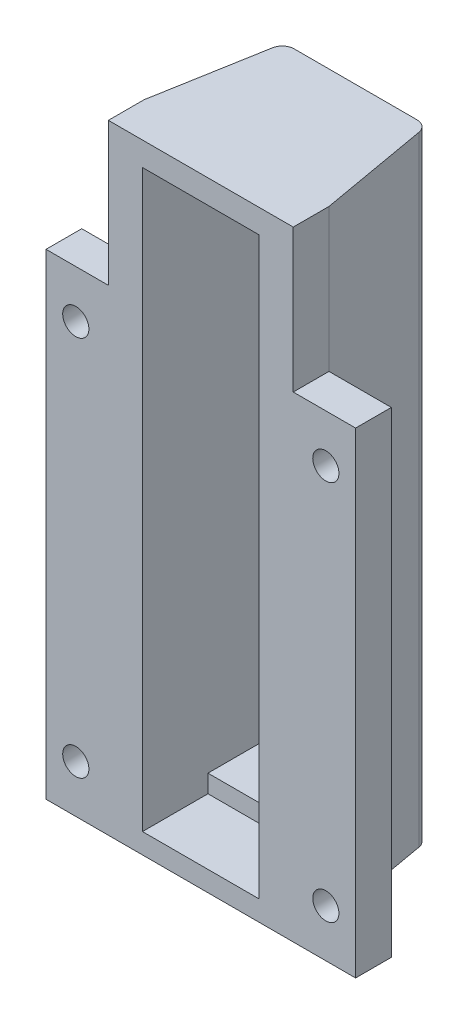
SolidWorks part; units mm, degrees
ref_plane "前视基准面" through (0, 0, 0) normal (0, 0, 1) x (1, 0, 0)
ref_plane "上视基准面" through (0, 0, 0) normal (0, 1, 0) x (1, 0, 0)
ref_plane "右视基准面" through (0, 0, 0) normal (1, 0, 0) x (0, 0, -1)
sketch "草图1" plane through (0, 0, 0) normal (0, 1, 0) x (1, 0, 0)
  line L0 (0, 0) -> (0, 11.5) construction
  line L1 (-13, -1.5) -> (13, -1.5)
  line L2 (-13, -1.5) -> (-13, 1.5)
  line L3 (-13, 1.5) -> (13, 1.5)
  line L4 (13, -1.5) -> (13, 1.5)
  line L5 (-13, -1.5) -> (13, 1.5) construction
  line L6 (-13, 1.5) -> (13, -1.5) construction
  line L7 (-6, 11.5) -> (6, 11.5)
  line L8 (6, 11.5) -> (8.2923, -1.5)
  line L9 (-6, 11.5) -> (-8.2923, -1.5)
  point P0 (0, 0)
  dimension "D1" = 26
  dimension "D2" = 3
  dimension "D3" = 80
  dimension "D4" = 12
  dimension "D5" = 13
extrude "凸台-拉伸1" add sketch "草图1" along normal blind 40 contours L7 L9 L3 L8 | L3 L9 L1 L8 | L9 L3 L2 L1 | L3 L8 L1 L4
sketch "草图2" plane through (0, 40, 0) normal (0, 1, 0) x (1, 0, 0)
  line L0 (6, 11.5) -> (7.7633, 1.5) construction
  line L1 (-6, 11.5) -> (6, 11.5) construction
  line L2 (-6, 11.5) -> (-7.7633, 1.5) construction
  line L3 (6, 11.5) -> (7.7633, 1.5)
  line L4 (-6, 11.5) -> (6, 11.5)
  line L5 (-6, 11.5) -> (-7.7633, 1.5)
  line L6 (-7.7633, 1.5) -> (-7.7633, -1.5)
  line L7 (-13, -1.5) -> (13, -1.5) construction
  line L8 (-7.7633, -1.5) -> (7.7633, -1.5)
  line L9 (7.7633, -1.5) -> (7.7633, 1.5)
extrude "凸台-拉伸2" add sketch "草图2" along normal blind 12
sketch "草图3" plane through (0, 0, 1.5) normal (0, 0, 1) x (1, 0, 0)
  line L0 (0, 0) -> (0, 25.85) construction
  line L1 (-7.7633, 52) -> (7.7633, 52) construction
  line L2 (-4.9, 3.2) -> (4.9, 3.2)
  line L3 (-4.9, 3.2) -> (-4.9, 48.5)
  line L4 (-4.9, 48.5) -> (4.9, 48.5)
  line L5 (4.9, 3.2) -> (4.9, 48.5)
  line L6 (-4.9, 3.2) -> (4.9, 48.5) construction
  line L7 (-4.9, 48.5) -> (4.9, 3.2) construction
  dimension "D1" = 9.8
  dimension "D2" = 45.3
  dimension "D3" = 3.5
extrude "切除-拉伸1" cut sketch "草图3" against normal offset from surface (10 mm away) 3 up to face at (0, 26, -11.5)
sketch "草图4" plane through (0, 0, 1.5) normal (0, 0, 1) x (1, 0, 0)
  line L0 (0, 48.5) -> (0, 3.2) construction
  line L2 (-4.9, 1.7) -> (4.9, 1.7)
  line L3 (-4.9, 1.7) -> (-4.9, 50)
  line L4 (4.9, 3.2) -> (4.9, 48.5)
  line L5 (4.9, 48.5) -> (-4.9, 48.5)
  line L6 (-4.9, 48.5) -> (-4.9, 3.2)
  line L7 (-4.9, 3.2) -> (4.9, 3.2)
  line L8 (4.9, 3.2) -> (4.9, 48.5) construction
  line L9 (4.9, 48.5) -> (-4.9, 48.5) construction
  line L10 (-4.9, 48.5) -> (-4.9, 3.2) construction
  line L11 (-4.9, 3.2) -> (4.9, 3.2) construction
  line L12 (-4.9, 50) -> (4.9, 50)
  line L13 (4.9, 1.7) -> (4.9, 50)
  line L14 (-4.9, 1.7) -> (4.9, 50) construction
  line L15 (-4.9, 50) -> (4.9, 1.7) construction
  point P6 (0, 25.85)
  point P11 (6.2017, 50)
  dimension "D2" = 1.5
  dimension "D1" = 0
extrude "切除-拉伸2" cut sketch "草图4" against normal offset from surface (5.5 mm away) 4.5 up to face at (0, 25.85, -8.5)
sketch "草图5" plane through (0, 0, 1.5) normal (0, 0, 1) x (1, 0, 0)
  line L0 (-13, 20) -> (19.9241, 20) construction
  line L1 (-13, 40) -> (-13, 0) construction
  line L2 (0, 0) -> (0, 29.4986) construction
  line L3 (-13, 40) -> (-7.7633, 40) construction
  circle A0 centre (-10.5, 36) radius 1.1
  circle A1 centre (-10.5, 4) radius 1.1
  circle A2 centre (10.5, 4) radius 1.1
  circle A3 centre (10.5, 36) radius 1.1
  dimension "D1" = 2.2
  dimension "D2" = 2.5
  dimension "D3" = 4
extrude "切除-拉伸3" cut sketch "草图5" against normal through all
sketch "草图6" plane through (0, 0, -8.5) normal (0, 0, 1) x (1, 0, 0)
  line L0 (0, 48.5) -> (0, 3.2) construction
  line L2 (-1.75, 8.35) -> (1.75, 8.35)
  line L3 (-1.75, 8.35) -> (-1.75, 43.35)
  line L4 (4.9, 3.2) -> (4.9, 48.5)
  line L5 (4.9, 48.5) -> (-4.9, 48.5)
  line L6 (-4.9, 48.5) -> (-4.9, 3.2)
  line L7 (-4.9, 3.2) -> (4.9, 3.2)
  line L8 (4.9, 3.2) -> (4.9, 48.5) construction
  line L9 (4.9, 48.5) -> (-4.9, 48.5) construction
  line L10 (-4.9, 48.5) -> (-4.9, 3.2) construction
  line L11 (-4.9, 3.2) -> (4.9, 3.2) construction
  line L12 (-1.75, 43.35) -> (1.75, 43.35)
  line L13 (1.75, 8.35) -> (1.75, 43.35)
  line L14 (-1.75, 8.35) -> (1.75, 43.35) construction
  line L15 (-1.75, 43.35) -> (1.75, 8.35) construction
  point P6 (0, 25.85)
  dimension "D2" = 3.5
  dimension "D3" = 35
  dimension "D1" = 0
extrude "切除-拉伸4" cut sketch "草图6" against normal through all
sketch "草图7" plane through (0, 0, -8.5) normal (0, 0, 1) x (1, 0, 0)
  line L0 (0, 8.35) -> (0, 46.35) construction
  line L1 (-1.75, 8.35) -> (1.75, 8.35) construction
  line L2 (1.75, 25.85) -> (15.714, 25.85) construction
  line L3 (1.75, 8.35) -> (1.75, 43.35) construction
  circle A0 centre (0, 46.35) radius 1.1
  circle A1 centre (0, 5.35) radius 1.1
  dimension "D1" = 2.2
  dimension "D2" = 41
extrude "切除-拉伸5" cut sketch "草图7" against normal through all
sketch "草图8" plane through (0, 0, -11.5) normal (0, 0, -1) x (-1, 0, 0)
  circle A0 centre (0, 46.35) radius 1.1 construction
  circle A1 centre (0, 46.35) radius 1.1 construction
  circle A2 centre (0, 5.35) radius 1.1 construction
  circle A3 centre (0, 5.35) radius 1.1 construction
  circle A4 centre (0, 46.35) radius 1.95
  circle A5 centre (0, 5.35) radius 1.95
  dimension "D1" = 3.9
extrude "切除-拉伸6" cut sketch "草图8" against normal blind 1.2
chamfer "倒角1" [suppressed] distance 5.24 angle 45
fillet "圆角2" radius 1 2 edges at (6, 26, -11.5) (-6, 26, -11.5)
